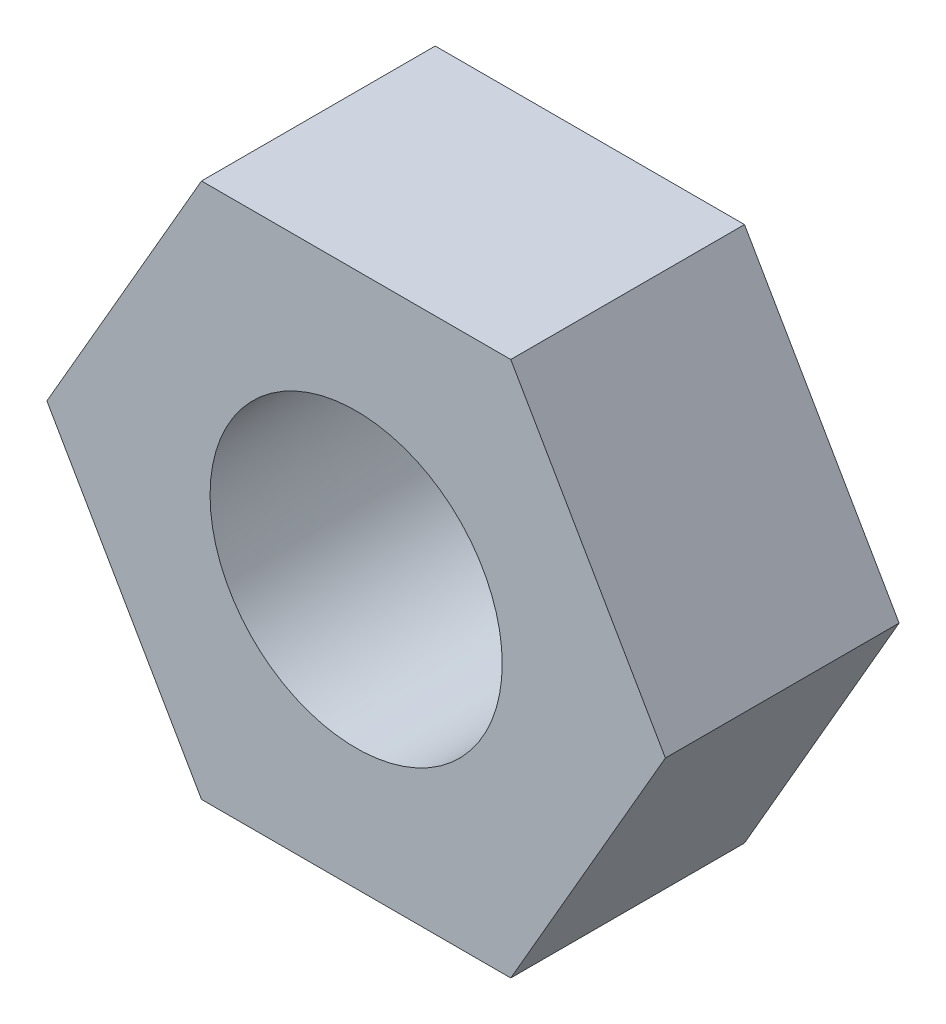
SolidWorks part; units mm, degrees
ref_plane "前视基准面" through (0, 0, 0) normal (0, 0, 1) x (1, 0, 0)
ref_plane "上视基准面" through (0, 0, 0) normal (0, 1, 0) x (1, 0, 0)
ref_plane "右视基准面" through (0, 0, 0) normal (1, 0, 0) x (0, 0, -1)
other "Configuration Table"
sketch "草图1" plane through (0, 0, 0) normal (0, 0, 1) x (1, 0, 0)
  line L0 (3.1754, 0) -> (1.5877, 2.75)
  line L1 (1.5877, 2.75) -> (-1.5877, 2.75)
  line L2 (-1.5877, 2.75) -> (-3.1754, 0)
  line L3 (-3.1754, 0) -> (-1.5877, -2.75)
  line L4 (-1.5877, -2.75) -> (1.5877, -2.75)
  line L5 (1.5877, -2.75) -> (3.1754, 0)
  circle A0 centre (0, 0) radius 1.5
extrude "标准对边_厚度_螺纹孔" add sketch "草图1" along normal blind 2.4
